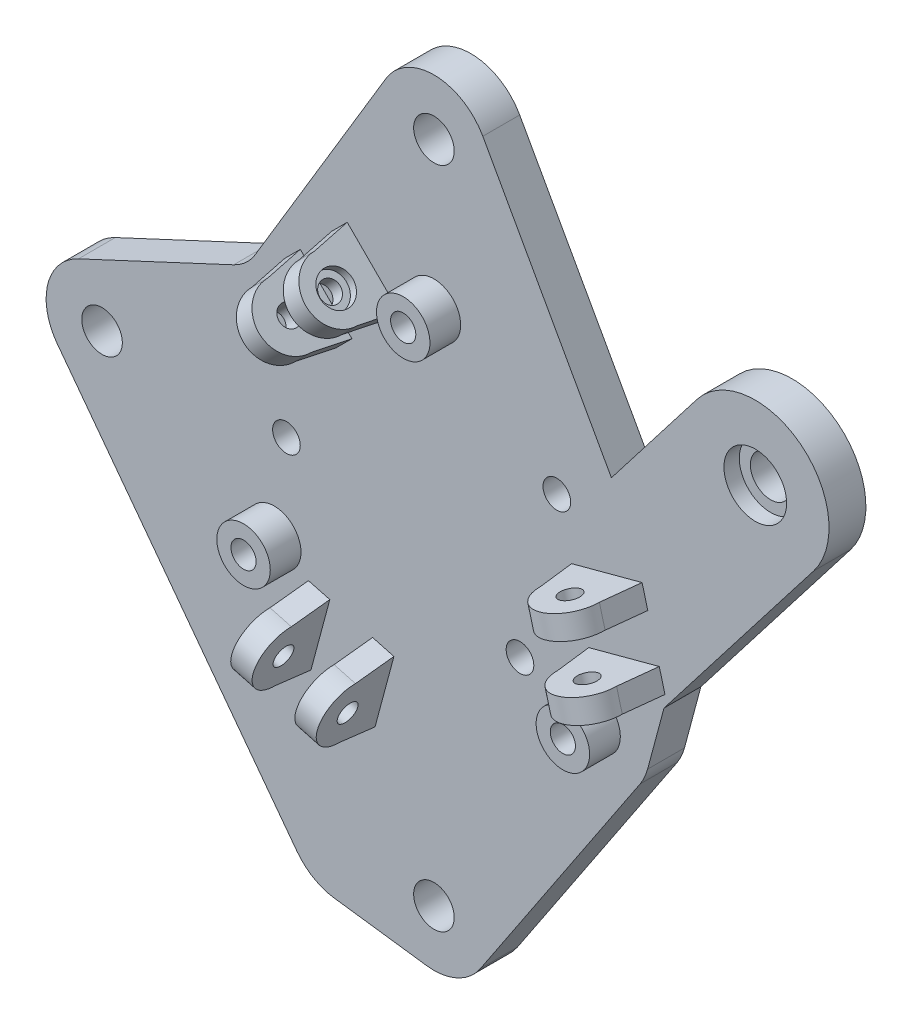
SolidWorks part; units mm, degrees
ref_plane "Front Plane" through (0, 0, 0) normal (0, 0, 1) x (1, 0, 0)
ref_plane "Top Plane" through (0, 0, 0) normal (0, 1, 0) x (1, 0, 0)
ref_plane "Right Plane" through (0, 0, 0) normal (1, 0, 0) x (0, 0, -1)
sketch "S01 - Rounded V3 backplate with cage and cassette fixings" plane through (0, 0, 0) normal (0, 0, 1) x (1, 0, 0)
  line L0 (-61.28, -5.46) -> (-22.28, -57.46)
  line L1 (-16.2027, -61.0202) -> (-1.2027, -63.0202)
  line L2 (7.5734, -59.0452) -> (33.5541, -20.0452)
  line L3 (34.7707, -17.3553) -> (38.7899, -2.3553)
  line L4 (37.9548, 4.4194) -> (7.9548, 58.4194)
  line L5 (-7.8032, 58.6819) -> (-29.1118, 23.1676)
  line L6 (-32.5886, 20.0341) -> (-57.8483, 8.2463)
  arc A0 (-57.8483, 8.2463) -> (-61.28, -5.46) centre (-54, 0) ccw
  arc A1 (-22.28, -57.46) -> (-16.2027, -61.0202) centre (-15, -52) ccw
  arc A2 (-1.2027, -63.0202) -> (7.5734, -59.0452) centre (0, -54) ccw
  arc A3 (33.5541, -20.0452) -> (34.7707, -17.3553) centre (25.9808, -15) ccw
  arc A4 (38.7899, -2.3553) -> (37.9548, 4.4194) centre (30, 0) ccw
  arc A5 (7.9548, 58.4194) -> (-7.8032, 58.6819) centre (0, 54) ccw
  arc A6 (-29.1118, 23.1676) -> (-32.5886, 20.0341) centre (-35.9717, 27.2836) cw
  circle A7 centre (0, 54) radius 3.3
  circle A8 centre (-54, 0) radius 3.3
  circle A9 centre (0, -54) radius 3.3
  circle A10 centre (14, -12) radius 2.25
  circle A11 centre (20, 14) radius 2.25
  circle A12 centre (-24, 0) radius 2.25
  dimension "D1" = 6.6
  dimension "D2" = 4.5
  dimension "D3" = 6.6
  dimension "D4" = 6.6
  dimension "D5" = 4.5
  dimension "D6" = 4.5
  dimension "D7" = 9.1
  dimension "D8" = 9.1
  dimension "D9" = 9.1
  dimension "D10" = 9.1
  dimension "D11" = 9.1
  dimension "D12" = 9.1
  dimension "D13" = 8
  dimension "D14" = 7.5734
  dimension "D15" = 7.9548
  dimension "D16" = 14
  dimension "D17" = 20
  dimension "D18" = 25.9808
  dimension "D19" = 30
  dimension "D20" = 33.5541
  dimension "D21" = 34.7707
  dimension "D22" = 37.9548
  dimension "D23" = 38.7899
  dimension "D24" = 1.2027
  dimension "D25" = 7.8032
  dimension "D26" = 15
  dimension "D27" = 16.2027
  dimension "D28" = 22.28
  dimension "D29" = 24
  dimension "D30" = 29.1118
  dimension "D31" = 32.5886
  dimension "D32" = 35.9717
  dimension "D33" = 54
  dimension "D34" = 57.8483
  dimension "D35" = 61.28
  dimension "D36" = 14
  dimension "D37" = 20.0341
  dimension "D38" = 54
  dimension "D39" = 15
  dimension "D40" = 52
  dimension "D41" = 54
  dimension "D43" = 12
extrude "01 - Rounded V3 backplate with cage and cassette fixings" add sketch "S01 - Rounded V3 backplate with cage and cassette fixings" along normal blind 6 from offset 12
sketch "S02 - Three cord guide pedestals" plane through (0, 0, 0) normal (0, 0, 1) x (1, 0, 0)
  circle A0 centre (25.9808, -15) radius 4.35
  circle A1 centre (0, 30) radius 4.35
  circle A2 centre (-25.9808, -15) radius 4.35
  dimension "D1" = 8.7
  dimension "D2" = 8.7
  dimension "D3" = 8.7
  dimension "D4" = 25.9808
  dimension "D5" = 25.9808
  dimension "D6" = 30
  dimension "D7" = 15
extrude "02 - Three cord guide pedestals" add sketch "S02 - Three cord guide pedestals" along normal blind 5 from offset 6
sketch "S03 - Three smooth grommet seats" plane through (0, 0, 0) normal (0, 0, 1) x (1, 0, 0)
  circle A0 centre (25.9808, -15) radius 2.05
  circle A1 centre (0, 30) radius 2.05
  circle A2 centre (-25.9808, -15) radius 2.05
  dimension "D1" = 4.1
  dimension "D2" = 4.1
  dimension "D3" = 4.1
  dimension "D4" = 25.9808
  dimension "D5" = 25.9808
  dimension "D6" = 30
  dimension "D7" = 15
extrude "03 - Three smooth grommet seats" cut sketch "S03 - Three smooth grommet seats" along normal blind 14 from offset 13 offset against normal yes
sketch3d "Plane points - Integral A1 fork cheek L"
  point P0 (30, 0, 0)
  point P1 (12.6133, -4.6587, 0)
  point P2 (30, 0, 18)
ref_plane "Drilling plane - Integral A1 fork cheek L" through (2.0096, -7.5, 0) normal (-0.2588, 0.9659, 0) x (0.9659, 0.2588, 0)
sketch "S04 - Integral A1 fork cheek L" plane through (2.0096, -7.5, 0) normal (-0.2588, 0.9659, 0) x (0.9659, 0.2588, 0)
  line L0 (35.0778, 7) -> (22.8778, 7)
  line L1 (22.8778, 7) -> (24.0278, 0)
  line L2 (33.9278, 0) -> (35.0778, 7)
  arc A0 (24.0278, 0) -> (33.9278, 0) centre (28.9778, 0) ccw
  dimension "D1" = 4.95
  dimension "D2" = 22.8778
  dimension "D3" = 28.9778
  dimension "D4" = 35.0778
  dimension "D5" = 7
extrude "04 - Integral A1 fork cheek L" add sketch "S04 - Integral A1 fork cheek L" along normal blind 3.6 from offset 7.2
sketch3d "Plane points - Integral A1 fork cheek R"
  point P0 (30, 0, 0)
  point P1 (12.6133, -4.6587, 0)
  point P2 (30, 0, 18)
ref_plane "Drilling plane - Integral A1 fork cheek R" through (2.0096, -7.5, 0) normal (-0.2588, 0.9659, 0) x (0.9659, 0.2588, 0)
sketch "S05 - Integral A1 fork cheek R" plane through (2.0096, -7.5, 0) normal (-0.2588, 0.9659, 0) x (0.9659, 0.2588, 0)
  line L0 (35.0778, 7) -> (22.8778, 7)
  line L1 (22.8778, 7) -> (24.0278, 0)
  line L2 (33.9278, 0) -> (35.0778, 7)
  arc A0 (24.0278, 0) -> (33.9278, 0) centre (28.9778, 0) ccw
  dimension "D1" = 4.95
  dimension "D2" = 22.8778
  dimension "D3" = 28.9778
  dimension "D4" = 35.0778
  dimension "D5" = 7
extrude "05 - Integral A1 fork cheek R" add sketch "S05 - Integral A1 fork cheek R" along normal blind 3.6 from offset 3.6
sketch3d "Plane points - A1 pivot through both cheeks"
  point P0 (30, 0, 0)
  point P1 (12.6133, -4.6587, 0)
  point P2 (30, 0, 18)
ref_plane "Drilling plane - A1 pivot through both cheeks" through (2.0096, -7.5, 0) normal (-0.2588, 0.9659, 0) x (0.9659, 0.2588, 0)
sketch "S06 - A1 pivot through both cheeks" plane through (2.0096, -7.5, 0) normal (-0.2588, 0.9659, 0) x (0.9659, 0.2588, 0)
  circle A0 centre (28.9778, 0) radius 1.65
  dimension "D1" = 3.3
  dimension "D2" = 28.9778
extrude "06 - A1 pivot through both cheeks" cut sketch "S06 - A1 pivot through both cheeks" along normal blind 15 from offset 7.5 offset against normal yes
sketch3d "Plane points - A1 recessed pivot screw head"
  point P0 (30, 0, 0)
  point P1 (12.6133, -4.6587, 0)
  point P2 (30, 0, 18)
ref_plane "Drilling plane - A1 recessed pivot screw head" through (2.0096, -7.5, 0) normal (-0.2588, 0.9659, 0) x (0.9659, 0.2588, 0)
sketch "S07 - A1 recessed pivot screw head" plane through (2.0096, -7.5, 0) normal (-0.2588, 0.9659, 0) x (0.9659, 0.2588, 0)
  circle A0 centre (28.9778, 0) radius 2.7
  dimension "D1" = 5.4
  dimension "D2" = 28.9778
extrude "07 - A1 recessed pivot screw head" cut sketch "S07 - A1 recessed pivot screw head" along normal blind 1.5 from offset 7.3 offset against normal yes
sketch3d "Plane points - Integral A2 fork cheek L"
  point P0 (-15, 25.9808, 0)
  point P1 (-2.2721, 13.2528, 0)
  point P2 (-15, 25.9808, 18)
ref_plane "Drilling plane - Integral A2 fork cheek L" through (5.4904, 5.4904, 0) normal (-0.7071, -0.7071, 0) x (-0.7071, 0.7071, 0)
sketch "S08 - Integral A2 fork cheek L" plane through (5.4904, 5.4904, 0) normal (-0.7071, -0.7071, 0) x (-0.7071, 0.7071, 0)
  line L0 (35.0778, 7) -> (22.8778, 7)
  line L1 (22.8778, 7) -> (24.0278, 0)
  line L2 (33.9278, 0) -> (35.0778, 7)
  arc A0 (24.0278, 0) -> (33.9278, 0) centre (28.9778, 0) ccw
  dimension "D1" = 4.95
  dimension "D2" = 22.8778
  dimension "D3" = 28.9778
  dimension "D4" = 35.0778
  dimension "D5" = 7
extrude "08 - Integral A2 fork cheek L" add sketch "S08 - Integral A2 fork cheek L" along normal blind 3.6 from offset 7.2
sketch3d "Plane points - Integral A2 fork cheek R"
  point P0 (-15, 25.9808, 0)
  point P1 (-2.2721, 13.2528, 0)
  point P2 (-15, 25.9808, 18)
ref_plane "Drilling plane - Integral A2 fork cheek R" through (5.4904, 5.4904, 0) normal (-0.7071, -0.7071, 0) x (-0.7071, 0.7071, 0)
sketch "S09 - Integral A2 fork cheek R" plane through (5.4904, 5.4904, 0) normal (-0.7071, -0.7071, 0) x (-0.7071, 0.7071, 0)
  line L0 (35.0778, 7) -> (22.8778, 7)
  line L1 (22.8778, 7) -> (24.0278, 0)
  line L2 (33.9278, 0) -> (35.0778, 7)
  arc A0 (24.0278, 0) -> (33.9278, 0) centre (28.9778, 0) ccw
  dimension "D1" = 4.95
  dimension "D2" = 22.8778
  dimension "D3" = 28.9778
  dimension "D4" = 35.0778
  dimension "D5" = 7
extrude "09 - Integral A2 fork cheek R" add sketch "S09 - Integral A2 fork cheek R" along normal blind 3.6 from offset 3.6
sketch3d "Plane points - A2 pivot through both cheeks"
  point P0 (-15, 25.9808, 0)
  point P1 (-2.2721, 13.2528, 0)
  point P2 (-15, 25.9808, 18)
ref_plane "Drilling plane - A2 pivot through both cheeks" through (5.4904, 5.4904, 0) normal (-0.7071, -0.7071, 0) x (-0.7071, 0.7071, 0)
sketch "S10 - A2 pivot through both cheeks" plane through (5.4904, 5.4904, 0) normal (-0.7071, -0.7071, 0) x (-0.7071, 0.7071, 0)
  circle A0 centre (28.9778, 0) radius 1.65
  dimension "D1" = 3.3
  dimension "D2" = 28.9778
extrude "10 - A2 pivot through both cheeks" cut sketch "S10 - A2 pivot through both cheeks" along normal blind 15 from offset 7.5 offset against normal yes
sketch3d "Plane points - A2 recessed pivot screw head"
  point P0 (-15, 25.9808, 0)
  point P1 (-2.2721, 13.2528, 0)
  point P2 (-15, 25.9808, 18)
ref_plane "Drilling plane - A2 recessed pivot screw head" through (5.4904, 5.4904, 0) normal (-0.7071, -0.7071, 0) x (-0.7071, 0.7071, 0)
sketch "S11 - A2 recessed pivot screw head" plane through (5.4904, 5.4904, 0) normal (-0.7071, -0.7071, 0) x (-0.7071, 0.7071, 0)
  circle A0 centre (28.9778, 0) radius 2.7
  dimension "D1" = 5.4
  dimension "D2" = 28.9778
extrude "11 - A2 recessed pivot screw head" cut sketch "S11 - A2 recessed pivot screw head" along normal blind 1.5 from offset 7.3 offset against normal yes
sketch3d "Plane points - Integral A3 fork cheek L"
  point P0 (-15, -25.9808, 0)
  point P1 (-10.3413, -8.5941, 0)
  point P2 (-15, -25.9808, 18)
ref_plane "Drilling plane - Integral A3 fork cheek L" through (-7.5, 2.0096, 0) normal (0.9659, -0.2588, 0) x (0, 0, -1)
sketch "S12 - Integral A3 fork cheek L" plane through (-7.5, 2.0096, 0) normal (0.9659, -0.2588, 0) x (0, 0, -1)
  line L0 (7, -35.0778) -> (7, -22.8778)
  line L1 (7, -22.8778) -> (0, -24.0278)
  line L2 (0, -33.9278) -> (7, -35.0778)
  arc A0 (0, -24.0278) -> (0, -33.9278) centre (0, -28.9778) ccw
  dimension "D1" = 4.95
  dimension "D2" = 7
  dimension "D3" = 22.8778
  dimension "D4" = 28.9778
  dimension "D5" = 35.0778
extrude "12 - Integral A3 fork cheek L" add sketch "S12 - Integral A3 fork cheek L" along normal blind 3.6 from offset 7.2
sketch3d "Plane points - Integral A3 fork cheek R"
  point P0 (-15, -25.9808, 0)
  point P1 (-10.3413, -8.5941, 0)
  point P2 (-15, -25.9808, 18)
ref_plane "Drilling plane - Integral A3 fork cheek R" through (-7.5, 2.0096, 0) normal (0.9659, -0.2588, 0) x (0, 0, -1)
sketch "S13 - Integral A3 fork cheek R" plane through (-7.5, 2.0096, 0) normal (0.9659, -0.2588, 0) x (0, 0, -1)
  line L0 (7, -35.0778) -> (7, -22.8778)
  line L1 (7, -22.8778) -> (0, -24.0278)
  line L2 (0, -33.9278) -> (7, -35.0778)
  arc A0 (0, -24.0278) -> (0, -33.9278) centre (0, -28.9778) ccw
  dimension "D1" = 4.95
  dimension "D2" = 7
  dimension "D3" = 22.8778
  dimension "D4" = 28.9778
  dimension "D5" = 35.0778
extrude "13 - Integral A3 fork cheek R" add sketch "S13 - Integral A3 fork cheek R" along normal blind 3.6 from offset 3.6
sketch3d "Plane points - A3 pivot through both cheeks"
  point P0 (-15, -25.9808, 0)
  point P1 (-10.3413, -8.5941, 0)
  point P2 (-15, -25.9808, 18)
ref_plane "Drilling plane - A3 pivot through both cheeks" through (-7.5, 2.0096, 0) normal (0.9659, -0.2588, 0) x (0, 0, -1)
sketch "S14 - A3 pivot through both cheeks" plane through (-7.5, 2.0096, 0) normal (0.9659, -0.2588, 0) x (0, 0, -1)
  circle A0 centre (0, -28.9778) radius 1.65
  dimension "D1" = 3.3
  dimension "D2" = 28.9778
extrude "14 - A3 pivot through both cheeks" cut sketch "S14 - A3 pivot through both cheeks" along normal blind 15 from offset 7.5 offset against normal yes
sketch3d "Plane points - A3 recessed pivot screw head"
  point P0 (-15, -25.9808, 0)
  point P1 (-10.3413, -8.5941, 0)
  point P2 (-15, -25.9808, 18)
ref_plane "Drilling plane - A3 recessed pivot screw head" through (-7.5, 2.0096, 0) normal (0.9659, -0.2588, 0) x (0, 0, -1)
sketch "S15 - A3 recessed pivot screw head" plane through (-7.5, 2.0096, 0) normal (0.9659, -0.2588, 0) x (0, 0, -1)
  circle A0 centre (0, -28.9778) radius 2.7
  dimension "D1" = 5.4
  dimension "D2" = 28.9778
extrude "15 - A3 recessed pivot screw head" cut sketch "S15 - A3 recessed pivot screw head" along normal blind 1.5 from offset 7.3 offset against normal yes
sketch "S16 - Continuous land for bump end support" plane through (0, 0, 0) normal (0, 0, 1) x (1, 0, 0)
  line L0 (18.5061, 7.3393) -> (42.7933, 38.7566)
  line L1 (61.7811, 24.078) -> (37.4939, -7.3393)
  arc A0 (42.7933, 38.7566) -> (61.7811, 24.078) centre (52.2872, 31.4173) cw
  arc A1 (37.4939, -7.3393) -> (18.5061, 7.3393) centre (28, 0) cw
  dimension "D1" = 12
  dimension "D2" = 12
  dimension "D3" = 18.5061
  dimension "D4" = 28
  dimension "D5" = 37.4939
  dimension "D6" = 42.7933
  dimension "D7" = 52.2872
  dimension "D8" = 61.7811
  dimension "D9" = 24.078
extrude "16 - Continuous land for bump end support" add sketch "S16 - Continuous land for bump end support" along normal blind 6 from offset 12
sketch "S17 - Through clearance for track support screw" plane through (0, 0, 0) normal (0, 0, 1) x (1, 0, 0)
  circle A0 centre (52.2872, 31.4173) radius 3.3
  dimension "D1" = 6.6
  dimension "D2" = 52.2872
  dimension "D3" = 31.4173
extrude "17 - Through clearance for track support screw" cut sketch "S17 - Through clearance for track support screw" along normal blind 6.2 from offset 12.1 offset against normal yes
sketch "S18 - Locating counterbore for bump end post" plane through (0, 0, 0) normal (0, 0, 1) x (1, 0, 0)
  circle A0 centre (52.2872, 31.4173) radius 5.1
  dimension "D1" = 10.2
  dimension "D2" = 52.2872
  dimension "D3" = 31.4173
extrude "18 - Locating counterbore for bump end post" cut sketch "S18 - Locating counterbore for bump end post" along normal blind 2.6 from offset 8.5
